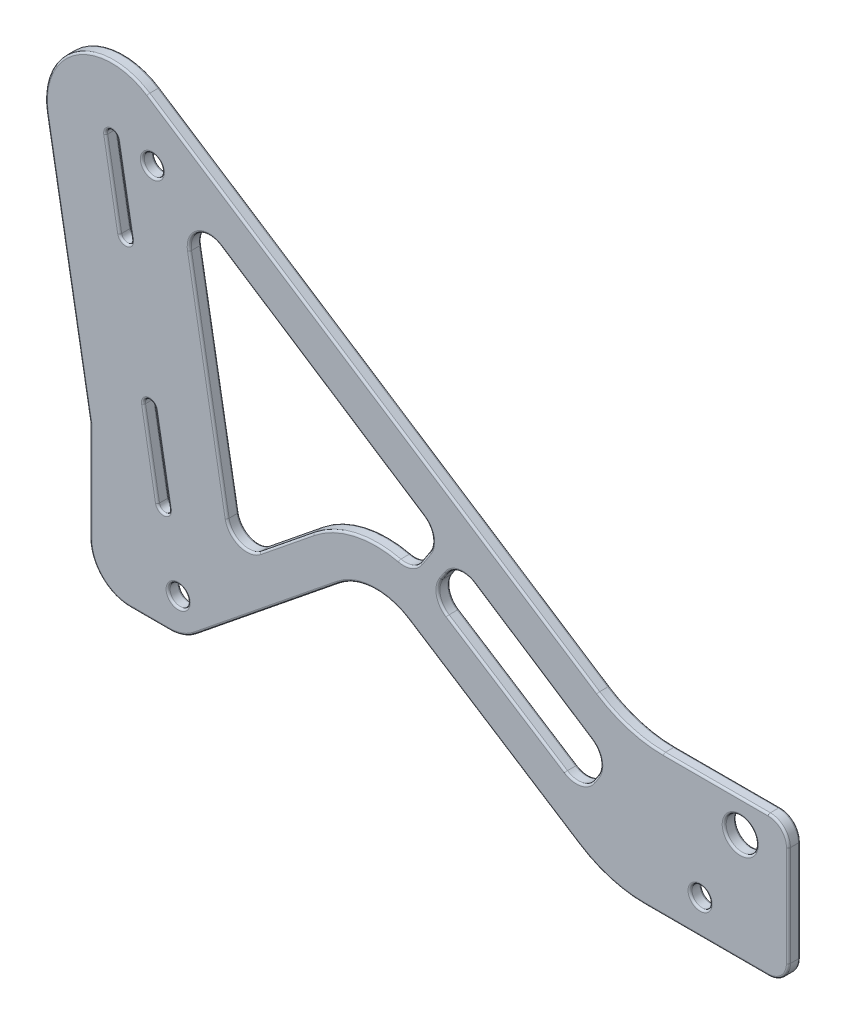
SolidWorks part; units mm, degrees
material "Plain Carbon Steel"
ref_plane "Front Plane" through (0, 0, 0) normal (0, 0, 1) x (1, 0, 0)
ref_plane "Top Plane" through (0, 0, 0) normal (0, 1, 0) x (1, 0, 0)
ref_plane "Right Plane" through (0, 0, 0) normal (1, 0, 0) x (0, 0, -1)
sketch "Sketch1" plane through (0, 0, 0) normal (0, 0, 1) x (1, 0, 0)
  line L1 (0, 35) -> (-136.4909, 35)
  line L2 (0, 35) -> (0, 0) construction
  line L3 (0, 0) -> (-170, 0)
  line L6 (-166.0314, 98.8743) -> (-162.5584, 79.1782)
  line L7 (-180.8035, 96.2696) -> (-170, 35)
  line L9 (-47.7694, 35) -> (0, 35)
  line L11 (0, 35) -> (0, 21.3542)
  line L12 (-170, 0) -> (-170, 35)
  line L13 (-163.0769, 99.3953) -> (-159.604, 79.6991)
  line L14 (-148.3048, 102) -> (-136.4909, 35)
  line L15 (-148.3048, 102) -> (-180.8035, 96.2696) construction
  line L16 (-148.7071, 24.5) -> (-158.2144, 24.5) construction
  line L17 (-155.539, 112.9542) -> (-36.042, 35)
  line L18 (-164.5542, 99.1348) -> (-167.4194, 115.3841) construction
  line L19 (-153.6543, 45.9566) -> (-150.1813, 26.2605)
  line L20 (-156.6087, 45.4357) -> (-153.1357, 25.7395)
  line L21 (0, 35) -> (4, 35)
  line L22 (4, 35) -> (4, 0)
  line L23 (4, 0) -> (0, 0)
  circle A0 centre (-8, 27) radius 4
  arc A25 (-153.1357, 25.7395) -> (-150.1813, 26.2605) centre (-151.6585, 26) ccw
  arc A26 (-163.0769, 99.3953) -> (-166.0314, 98.8743) centre (-164.5542, 99.1348) ccw
  arc A27 (-148.3048, 102) -> (-180.8035, 96.2696) centre (-164.5542, 99.1348) ccw
  arc A30 (-162.5584, 79.1782) -> (-159.604, 79.6991) centre (-161.0812, 79.4387) ccw
  arc A31 (-153.6543, 45.9566) -> (-156.6087, 45.4357) centre (-155.1315, 45.6962) ccw
  circle A33 centre (-18, 8.5) radius 2.5
  circle A34 centre (-148, 8.5) radius 2.5
  dimension "D6" = 3
  dimension "D7" = 15
  dimension "D8" = 20
  dimension "D9" = 100
  dimension "D16" = 4
  dimension "D17" = 5
  dimension "D18" = 22
  dimension "D37" = 8
  dimension "D11" = 9
  dimension "D12" = 20
  dimension "D14" = 8.5
  dimension "D15" = 5
  dimension "D2" = 35
  dimension "D3" = 8
  dimension "D4" = 8
  dimension "D5" = 170
  dimension "D10" = 22
  dimension "D13" = 67
extrude "Boss-Extrude1" add sketch "Sketch1" along normal blind 3
fillet "Fillet1" radius 5
other "Graphic1"
other "Graphic (Closed) -1"
other "Graphic (Closed) -2"
sketch "Sketch2" plane through (0, 0, 0) normal (0, 0, 1) x (1, 0, 0)
  line L0 (-40.7063, 0) -> (-90.6375, 32.0202)
  line L1 (-1, 0) -> (-170, 0) construction
  line L2 (-108.1594, 31.0631) -> (-146.6219, 0)
  line L3 (-146.6219, 0) -> (-40.7063, 0)
  arc A7 (-90.6375, 32.0202) -> (-108.1594, 31.0631) centre (-98.7348, 19.3935) ccw
  point P38 (-99.7436, 37.8598)
  dimension "D3" = 15
extrude "Cut-Extrude1" cut sketch "Sketch2" along normal blind 10
sketch "Sketch3" plane through (0, 0, 0) normal (0, 0, -1) x (-1, 0, 0)
  line L0 (74.3173, 48.0293) -> (45.0033, 28.9062)
  line L1 (43.5475, 21.9867) -> (44.6474, 20.3005)
  line L2 (145.1657, 84.1972) -> (135.8074, 31.1235)
  line L3 (114.4424, 38.8427) -> (152.9049, 7.7797)
  line L4 (114.4424, 38.8427) -> (127.7418, 28.1019)
  line L5 (153.6543, 45.9566) -> (150.1813, 26.2605) construction
  line L11 (85.4245, 49.3053) -> (87.6703, 45.8628)
  line L12 (81.2368, 46.5734) -> (82.486, 44.6585)
  line L14 (163.0769, 99.3953) -> (159.604, 79.6991) construction
  line L18 (37.7753, 10) -> (85.2393, 40.438)
  line L19 (114.4424, 38.8427) -> (150.1557, 10)
  line L20 (150.1557, 10) -> (160, 10)
  line L21 (160, 10) -> (160, 35.8749)
  line L22 (160, 35.8749) -> (170.9554, 98.0061)
  line L23 (161.0027, 104.5788) -> (39.0154, 25)
  line L24 (39.0154, 25) -> (6, 25)
  line L25 (6, 25) -> (6, 10)
  line L26 (6, 10) -> (37.7753, 10)
  line L27 (51.5343, 18.8234) -> (80.9974, 37.7178)
  line L32 (137.5098, 89.2531) -> (86.8804, 56.2249)
  arc A0 (85.4245, 49.3053) -> (86.8804, 56.2249) centre (89.6123, 52.0372) cw
  arc A1 (87.6703, 45.8628) -> (93.0041, 43.7278) centre (91.858, 48.5947) ccw
  arc A2 (80.9974, 37.7178) -> (82.486, 44.6585) centre (78.2983, 41.9267) ccw
  arc A3 (81.2368, 46.5734) -> (74.3173, 48.0293) centre (77.0491, 43.8416) ccw
  arc A7 (135.8074, 31.1235) -> (127.7418, 28.1019) centre (130.8833, 31.9917) cw
  arc A8 (114.4424, 38.8427) -> (85.2393, 40.438) centre (98.7348, 19.3935) ccw
  arc A9 (170.9554, 98.0061) -> (161.0027, 104.5788) centre (164.5542, 99.1348) ccw
  arc A10 (114.4424, 38.8427) -> (93.0041, 43.7278) centre (98.7348, 19.3935) ccw
  arc A11 (145.1657, 84.1972) -> (137.5098, 89.2531) centre (140.2417, 85.0654) ccw
  arc A12 (51.5343, 18.8234) -> (44.6474, 20.3005) centre (48.8352, 23.0323) cw
  arc A13 (45.0033, 28.9062) -> (43.5475, 21.9867) centre (47.7352, 24.7185) ccw
  point P27 (78.505, 50.7611)
  dimension "D2" = 10
  dimension "D4" = 5
  dimension "D6" = 5
  dimension "D7" = 5
  dimension "D3" = 5
  dimension "D5" = 15
  dimension "D8" = 45
  dimension "D1" = 10
extrude "Cut-Extrude2" cut sketch "Sketch3" against normal blind 10
fillet "Fillet3" radius 30
fillet "Fillet4" radius 10
fillet "Fillet5" radius 0.5
sketch "Sketch4" plane through (0, 0, 0) normal (0, 0, -1) x (-1, 0, 0)
  line L0 (143.2726, 89.6549) -> (173.3713, 112.4861) construction
  line L1 (160.8481, 89.634) -> (147.5599, 107.1521) construction
  line L2 (159.1116, 79.7859) -> (162.5845, 99.4821) construction
  line L3 (155.8122, 112.5355) -> (43.7862, 39.455) construction
  circle A0 centre (154.4188, 98.1098) radius 2.5
  arc A1 (145.6581, 84.1104) -> (137.2366, 89.6719) centre (140.2417, 85.0654) ccw construction
  arc A2 (180.3111, 96.3564) -> (155.8122, 112.5355) centre (164.5542, 99.1348) ccw construction
  circle A3 centre (154.4188, 98.1098) radius 5 construction
  dimension "D1" = 5
  dimension "D2" = 10
extrude "Cut-Extrude3" cut sketch "Sketch4" against normal blind 10
fillet "Fillet6" radius 0.5
